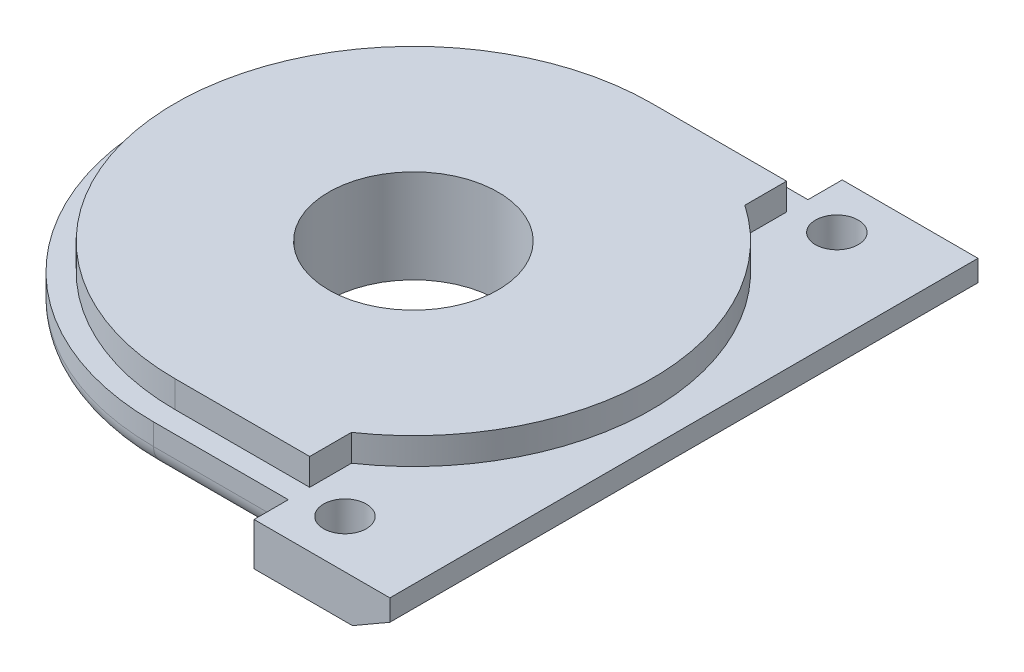
SolidWorks part; units mm, degrees
material "6061-T6 (SS)"
ref_plane "Front Plane" through (0, 0, 0) normal (0, 0, 1) x (1, 0, 0)
ref_plane "Top Plane" through (0, 0, 0) normal (0, 1, 0) x (1, 0, 0)
ref_plane "Right Plane" through (0, 0, 0) normal (1, 0, 0) x (0, 0, -1)
sketch "Sketch1" plane through (0, 0, 0) normal (0, 1, 0) x (1, 0, 0)
  line L0 (-13.2912, 20.8898) -> (-0.69, 20.8898)
  line L5 (-13.2912, -23.7056) -> (-0.69, -23.7056)
  line L7 (-0.69, -23.7056) -> (-0.69, -28.9079)
  line L8 (-0.69, -28.9079) -> (12.01, -28.9079)
  line L9 (-0.69, 20.8898) -> (-0.69, 26.0921)
  line L10 (12.01, -28.9079) -> (12.01, 26.0921)
  line L11 (12.01, 26.0921) -> (-0.69, 26.0921)
  arc A0 (-13.2912, 20.8898) -> (-13.2912, -23.7056) centre (-13.2912, -1.4079) ccw
extrude "Boss-Extrude1" add sketch "Sketch1" along normal blind 4
sketch "Sketch2" plane through (0, 4, 0) normal (0, 1, 0) x (1, 0, 0)
  line L4 (-13.2912, 20.8898) -> (-0.69, 20.8898)
  line L5 (-0.69, 20.8898) -> (-0.69, 16.9877)
  line L6 (-13.2912, -23.7056) -> (-0.69, -23.7056)
  line L7 (-0.69, -23.7056) -> (-0.69, -19.8035)
  arc A0 (-0.69, -19.8035) -> (-0.69, 16.9877) centre (-13.2912, -1.4079) ccw
  arc A1 (-13.2912, 20.8898) -> (-13.2912, -23.7056) centre (-13.2912, -1.4079) ccw
extrude "Boss-Extrude2" add sketch "Sketch2" along normal blind 2.5
sketch "Sketch3" plane through (0, 0, 0) normal (0, -1, 0) x (1, 0, 0)
  circle A0 centre (-13.2912, 1.4079) radius 7.925
  dimension "D1" = 15.85
extrude "Cut-Extrude1" cut sketch "Sketch3" against normal blind 9.25
sketch "Sketch4" plane through (0, 0, 0) normal (0, -1, 0) x (1, 0, 0)
  line L0 (3.31, -21.5921) -> (3.31, -26.0921) construction
  line L2 (12.01, -26.0921) -> (-0.69, -26.0921) construction
  line L3 (3.31, -26.0921) -> (-0.69, -26.0921) construction
  line L5 (3.31, 24.4079) -> (3.31, 28.9079) construction
  line L6 (-0.69, 28.9079) -> (12.01, 28.9079) construction
  line L7 (3.31, 28.9079) -> (-0.69, 28.9079) construction
  circle A0 centre (3.31, 24.4079) radius 2
  circle A1 centre (3.31, -21.5921) radius 2
  dimension "D1" = 4.5
  dimension "D2" = 4
  dimension "D4" = 4
  dimension "D3" = 4.5
extrude "Cut-Extrude2" cut sketch "Sketch4" against normal blind 9.25
sketch "Sketch5" plane through (0, 0, 0) normal (0, -1, 0) x (1, 0, 0)
  line L9 (-20.9013, 10.589) -> (-24.2357, 16.3644)
  line L12 (-17.4372, 12.589) -> (-20.7716, 18.3644)
  line L14 (-1.5351, 3.4079) -> (5.1338, 3.4079)
  line L17 (-1.5351, -0.5921) -> (5.1338, -0.5921)
  line L19 (-17.4372, -9.7732) -> (-20.7716, -15.5486)
  line L22 (-20.9013, -7.7732) -> (-24.2357, -13.5486)
  circle A2 centre (-13.2912, 1.4079) radius 11.925
  arc A3 (-1.5351, 3.4079) -> (-17.4372, 12.589) centre (-13.2912, 1.4079) ccw
  circle A4 centre (-13.2912, 1.4079) radius 18.425
  circle A5 centre (-13.2912, 1.4079) radius 18.425
  circle A6 centre (-13.2912, 1.4079) radius 18.425
  circle A7 centre (-13.2912, 1.4079) radius 18.425
  arc A8 (-20.9013, 10.589) -> (-20.9013, -7.7732) centre (-13.2912, 1.4079) ccw
  arc A9 (-17.4372, -9.7732) -> (-1.5351, -0.5921) centre (-13.2912, 1.4079) ccw
  point P14 (-13.2912, 1.4079)
  dimension "D1" = 4
  dimension "D2" = 10.5
  dimension "D3" = 3
extrude "Cut-Extrude3" cut sketch "Sketch5" against normal blind 3.25 contours A8 L9 A4 L22 | L14 A4 L12 A3 | A9 L19 A4 L17
fillet "Fillet1" radius 2.36 10 edges at (5.0249, 1.625, 3.4079) (-1.5351, 1.625, 3.4079) (5.0249, 1.625, -0.5921) (-24.1813, 1.625, 16.2701) (-20.7172, 1.625, 18.2701) (-1.5351, 1.625, -0.5921) (-20.7172, 1.625, -15.4543) (-20.9013, 1.625, 10.589) (-20.9013, 1.625, -7.7732) (-24.1813, 1.625, -13.4543)
chamfer "Chamfer1" distance 3.5 angle 30 1 edges at (12.01, 0, 1.4079)
sketch "Sketch10" plane through (0, 0, 0) normal (0, -1, 0) x (1, 0, 0)
  line L2 (-0.69, -22.8898) -> (-13.2912, -22.8898)
  line L3 (-13.2912, 25.7056) -> (-0.69, 25.7056)
  line L4 (-0.69, -20.8898) -> (-13.2912, -20.8898)
  line L5 (-13.2912, 23.7056) -> (-0.69, 23.7056)
  line L6 (-0.69, -20.8898) -> (-13.2912, -20.8898)
  line L7 (-13.2912, 23.7056) -> (-0.69, 23.7056)
  line L8 (-0.69, 25.7056) -> (-0.69, 23.7056)
  line L9 (-0.69, -20.8898) -> (-0.69, -22.8898)
  arc A1 (-13.2912, 25.7056) -> (-13.2912, -22.8898) centre (-13.2912, 1.4079) ccw
  arc A2 (-13.2912, 23.7056) -> (-13.2912, -20.8898) centre (-13.2912, 1.4079) ccw
  arc A3 (-13.2912, 23.7056) -> (-13.2912, -20.8898) centre (-13.2912, 1.4079) ccw
  dimension "D1" = 0
  dimension "D2" = 2
extrude "Boss-Extrude4" add sketch "Sketch10" against normal blind 4
fillet "Fillet4" radius 2 3 edges at (-6.9906, 0, 25.7056) (-6.9906, 0, -22.8898) (-37.5889, 0, 1.4079)
sketch "Sketch11" plane through (0, 0, 0) normal (0, -1, 0) x (1, 0, 0)
  circle A1 centre (-13.2912, 1.4079) radius 11.925
extrude "Boss-Extrude5" add sketch "Sketch11" along normal blind 2.25
sketch "Sketch12" plane through (0, 0, 0) normal (0, 1, 0) x (1, 0, 0)
  circle A2 centre (-13.2912, -1.4079) radius 7.925
  circle A3 centre (-13.2912, -1.4079) radius 7.925
  dimension "D1" = 0
extrude "Cut-Extrude4" cut sketch "Sketch12" against normal blind 2.25
